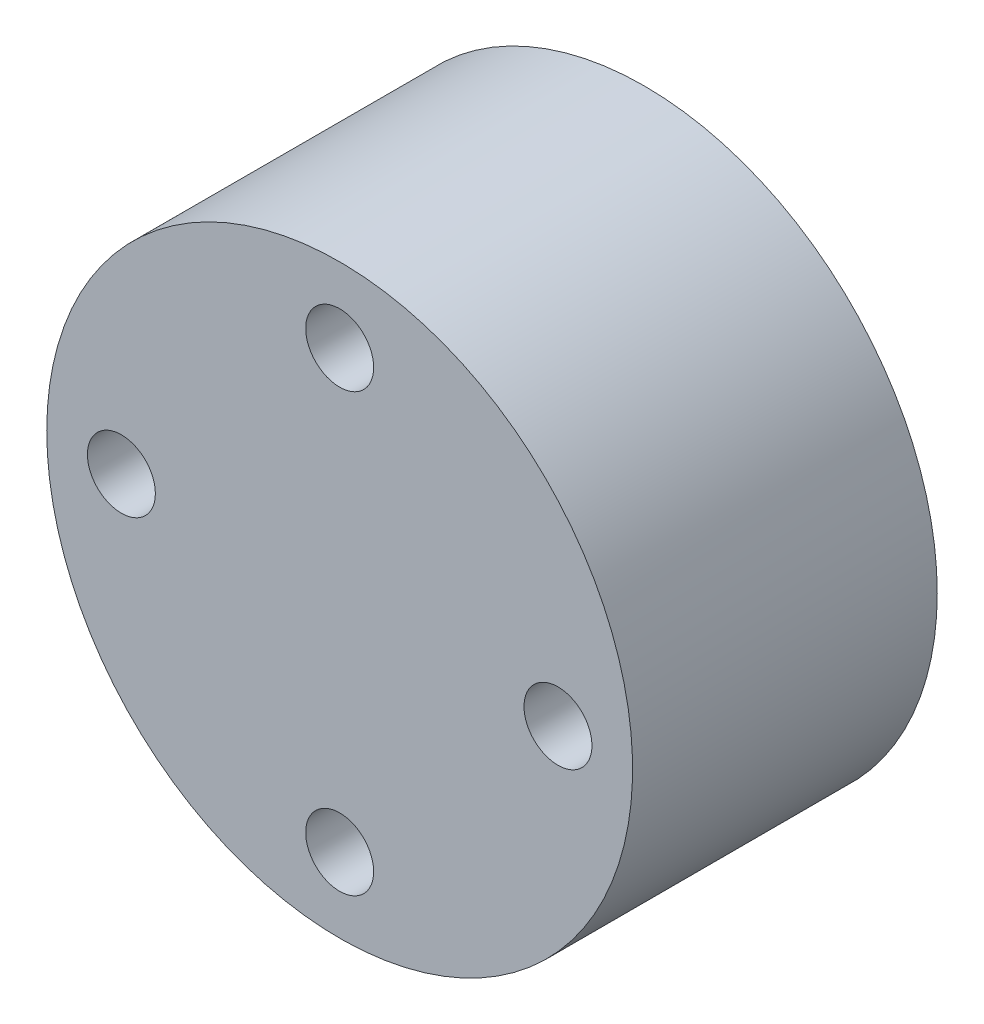
SolidWorks part; units mm, degrees
ref_plane "Front Plane" through (0, 0, 0) normal (0, 0, 1) x (1, 0, 0)
ref_plane "Top Plane" through (0, 0, 0) normal (0, 1, 0) x (1, 0, 0)
ref_plane "Right Plane" through (0, 0, 0) normal (1, 0, 0) x (0, 0, -1)
sketch "Sketch1" plane through (0, 0, 0) normal (0, 0, 1) x (1, 0, 0)
  circle A0 centre (0, 0) radius 12.5
  dimension "D1" = 25
extrude "Boss-Extrude1" add sketch "Sketch1" along normal mid plane 10
sketch "Sketch2" plane through (0, 0, 0) normal (1, 0, 0) x (0, 0, -1)
  line L0 (0, 0) -> (-9.3347, 0) construction
  line L1 (-8, 0) -> (-8, 12.5)
  line L3 (-5, 12.5) -> (-5, -12.5) construction
  line L4 (-5, 12.5) -> (-8, 12.5)
  line L5 (-5, 12.5) -> (-5, 0)
  line L6 (-5, 0) -> (-8, 0)
  dimension "D1" = 12.5
  dimension "D2" = 3
  dimension "D3" = 0
revolve "Revolve1" add sketch "Sketch2" angle 360 about L0
sketch "Sketch5" plane through (0, 0, 8) normal (0, 0, 1) x (1, 0, 0)
  circle A0 centre (0, 9.315) radius 1.45
  circle A1 centre (0, 9.315) radius 1.45 construction
  circle A2 centre (9.315, 0) radius 1.45
  circle A3 centre (0, -9.315) radius 1.45
  circle A4 centre (-9.315, 0) radius 1.45
  point P14 (0, 0)
  dimension "D1" = 0
  dimension "D2" = 4
extrude "Cut-Extrude1" cut sketch "Sketch5" against normal blind 5
sketch "Sketch6" plane through (0, 0, -5) normal (0, 0, -1) x (-1, 0, 0)
  circle A7 centre (0, 8) radius 1.45
  circle A8 centre (8, 0) radius 1.45
  circle A9 centre (0, -8) radius 1.45
  circle A10 centre (-8, 0) radius 1.45
  point P12 (0, 0)
  point P14 (0, 0)
  dimension "D1" = 2.9
  dimension "D2" = 4
  dimension "D3" = 16
extrude "Cut-Extrude2" cut sketch "Sketch6" against normal blind 5
